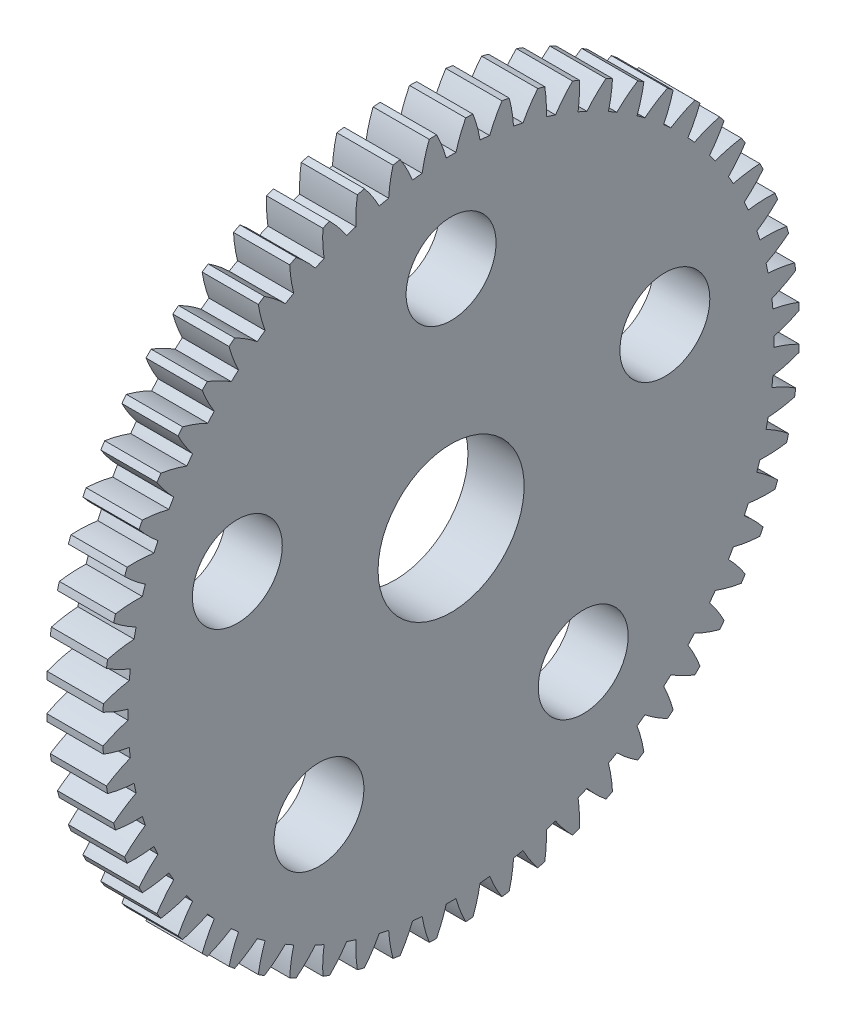
SolidWorks part; units mm, degrees
ref_plane "Plane1" through (0, 0, 0) normal (0, 0, 1) x (1, 0, 0)
ref_plane "Plane2" through (0, 0, 0) normal (0, 1, 0) x (1, 0, 0)
ref_plane "Plane3" through (0, 0, 0) normal (1, 0, 0) x (0, 0, -1)
sketch "HoldingSke" plane through (0, 0, 0) normal (0, 1, 0) x (1, 0, 0)
  line L0 (0, 0) -> (0.5, -0.866)
  line L1 (-15, 0) -> (100, 0) construction
  line L2 (0, 0) -> (-2.1039, 2.3779)
  line L3 (0, 0) -> (-11.863, 4.5341)
  line L4 (0, 0) -> (4.318, 7.479)
  line L5 (0, 0) -> (-46.8476, -17.4728)
  line L6 (0, 0) -> (-4.1448, -2.7965)
  line L7 (-2.1039, 2.3779) -> (8.6586, 51.2059)
  line L8 (-76.2, 54.61) -> (-75.7, 54.61)
  line L9 (-71.009, 38.7566) -> (-53.1078, 45.2721)
  line L10 (-76.2, 71.12) -> (104.1128, 71.12)
  line L11 (0, 0) -> (-5, 0)
  line L12 (-76.2, 101.6) -> (-76.162, 101.6)
  line L13 (24.9733, 27.94) -> (52.9518, 28.4284)
  line L14 (24.9733, 27.94) -> (24.9743, 27.94)
  line L15 (24.9733, 27.94) -> (100.4006, 29.5858)
  line L16 (-63.627, -1) -> (-12.827, -1)
  circle A0 centre (0, 0) radius 1.5
  circle A1 centre (0, 0) radius 28.749
  circle A2 centre (0, 0) radius 37.5
  circle A3 centre (0, 0) radius 1.5
  dimension "MHD" = 57.498
  dimension "Hub_dia" = 75
  dimension "Bore" = 3
  dimension "MBD" = 3
  dimension "Num_teeth" = 60
  dimension "Pitch" = 1
  dimension "Overall_len" = 50
  dimension "Show_teeth" = 60
  dimension "Thickness" = 5
  dimension "OAL" = 50.0001
  dimension "T_dim" = 0.5
  dimension "Ap" = 20
  dimension "H" = 19.05
  dimension "Pitch_radius" = 180.3128
  dimension "Width" = 5
  dimension "Backlash" = 0.038
  dimension "Addendum_fac" = 1
  dimension "Dedendum_fac" = 1.25
  dimension "Clearance_fac" = 0.25
  dimension "Dedendum_add" = 0.001
  dimension "Module" = 1
sketch "BasProSke" plane through (0, 0, 0) normal (0, 1, 0) x (1, 0, 0)
  line L0 (-10, 0) -> (60, 0) construction
  line L1 (0, 0) -> (0, 31)
  line L2 (0, 0) -> (5, 0)
  line L3 (5, 0) -> (5, 31)
  line L4 (5, 31) -> (0, 31)
  dimension "Thickness" = 5
  dimension "Diameter" = 62
revolve "Base-Revolve" add sketch "BasProSke" angle 360 about L0
sketch "TooCutSke" plane through (0, 0, 0) normal (1, 0, 0) x (0, 0, -1)
  line L1 (0, 0) -> (0, 107) construction
  line L2 (0, 0) -> (-0.8518, 29.9879) construction
  line L3 (0, 0) -> (-3.1393, 59.9006) construction
  line L4 (-0.8518, 29.9879) -> (-1.5696, 29.9503) construction
  arc A0 (0.4302, 28.7458) -> (-0.4302, 28.7458) centre (0, 0) ccw
  arc A1 (1.3127, 30.9976) -> (-1.3127, 30.9976) centre (0, 0) ccw
  circle A2 centre (0, 0) radius 30 construction
  circle A3 centre (0, 0) radius 28.1908 construction
  arc A4 (-0.4302, 28.7458) -> (-1.3127, 30.9976) centre (-11.9871, 25.5153) ccw
  arc A5 (1.3127, 30.9976) -> (0.4302, 28.7458) centre (11.9871, 25.5153) ccw
  dimension "Root_dia" = 57.498
  dimension "Overcut_dia" = 62.0508
  dimension "Pitch_dia" = 60
  dimension "Base_dia" = 56.3816
  dimension "Flank_rad" = 12
  dimension "Half_ang" = 3
  dimension "Half_CT" = 0.7188
extrude "ToothCut" cut sketch "TooCutSke" along normal through all
fillet "Breaks" [suppressed] radius 0.02
fillet "RootFillets" [suppressed] radius 0.251
pattern_circular "TeethCuts" count 60 over 360 about axis through (0, 0, 0) along (1, 0, 0) of "ToothCut", "RootFillets", "Breaks"
sketch "HubNeaOneSke" plane through (0, 0, 0) normal (-1, 0, 0) x (0, 0, 1)
  circle A0 centre (0, 0) radius 28.749
  dimension "Diameter" = 57.498
extrude "HubNearOne" [suppressed] add sketch "HubNeaOneSke" along normal blind 45.0001
sketch "HubNeaBotSke" plane through (0, 0, 0) normal (-1, 0, 0) x (0, 0, 1)
  circle A0 centre (0, 0) radius 28.749
  dimension "Diameter" = 57.498
extrude "HubNearBoth" [suppressed] add sketch "HubNeaBotSke" along normal blind 22.5
ref_plane "FarPln" through (5, 0, 0) normal (1, 0, 0) x (0, 0, -1)
sketch "HubFarSke" plane through (5, 0, 0) normal (1, 0, 0) x (0, 0, -1)
  circle A0 centre (0, 0) radius 28.749
  dimension "Diameter" = 57.498
extrude "HubFar" [suppressed] add sketch "HubFarSke" along normal blind 22.5
sketch "BorSke" plane through (0, 0, 0) normal (1, 0, 0) x (0, 0, -1)
  circle A0 centre (0, 0) radius 6.5
  dimension "Diameter" = 13
extrude "Bore" cut sketch "BorSke" along normal mid plane 100.0001
sketch "KeySke" plane through (0, 0, 0) normal (1, 0, 0) x (0, 0, -1)
  line L0 (-0.6, 0) -> (-0.6, 2)
  line L1 (-0.6, 2) -> (0.6, 2)
  line L2 (0.6, 2) -> (0.6, 0)
  line L3 (0, 0) -> (0, 34) construction
  line L4 (-0.6, 0) -> (0.6, 0)
  dimension "Offset" = 2
  dimension "Width" = 1.2
extrude "Keyway" [suppressed] cut sketch "KeySke" along normal mid plane 100.0001
sketch "草图1" plane through (5, 0, 0) normal (1, 0, 0) x (0, 0, -1)
  circle A0 centre (0, 20) radius 4
  circle A1 centre (0, 0) radius 6.5 construction
  circle A2 centre (19.0211, 6.1803) radius 4
  circle A3 centre (11.7557, -16.1803) radius 4
  circle A4 centre (-11.7557, -16.1803) radius 4
  circle A5 centre (-19.0211, 6.1803) radius 4
  point P14 (0, 0)
  dimension "D1" = 8
  dimension "D2" = 20
  dimension "D3" = 5
extrude "切除-拉伸2" cut sketch "草图1" against normal blind 5
equation "' \"Module@HoldingSke\" = 6.35"
equation "' \"Num_teeth@HoldingSke\" = 12"
equation "' \"Ap@HoldingSke\" =  20"
equation "' \"Ap@HoldingSke\" = 20"
equation "' \"Width@HoldingSke\" = 0.5 * 25.4"
equation "' \"Hub_dia@HoldingSke\"= 1 * 25.4"
equation "' \"Hub_dia@HoldingSke\" = 1 * 25.4"
equation "' \"Overall_len@HoldingSke\" = 1.0 * 25.4"
equation "' \"Bore@HoldingSke\" = 0.75 * 25.4"
equation "' \"T_dim@HoldingSke\" = 0.1 * 25.4"
equation "' \"Width@KeySke\" = 0.25 * 25.4"
equation "' \"Show_teeth@HoldingSke\" = 13"
equation "' \"Backlash@HoldingSke\" = 0.009 * 25.4"
equation "' \"Addendum_fac@HoldingSke\" = 1.0"
equation "' \"Dedendum_fac@HoldingSke\" = 1.25"
equation "' \"Dedendum_add@HoldingSke\" = 0.00005 * 25.4"
equation "' \"Clearance_fac@HoldingSke\" = 0.25"
equation "\"Pitch@HoldingSke\" = 1 / \"Module@HoldingSke\""
equation "\"Overcut_dia@TooCutSke\" = (\"Num_teeth@HoldingSke\" + 2 * \"Addendum_fac@HoldingSke\") / \"Pitch@HoldingSke\" + 0.002 * 25.4"
equation "\"Pitch_dia@TooCutSke\" = \"Num_teeth@HoldingSke\" / \"Pitch@HoldingSke\""
equation "\"Base_dia@TooCutSke\" = \"Num_teeth@HoldingSke\" / \"Pitch@HoldingSke\" * cos((\"Ap@HoldingSke\"  * 3.14159265 / 180))"
equation "\"Root_dia@TooCutSke\" = (\"Num_teeth@HoldingSke\" + 2) / \"Pitch@HoldingSke\" - 2 * (\"Addendum_fac@HoldingSke\" + \"Dedendum_fac@HoldingSke\") / \"Pitch@HoldingSke\" - \"Dedendum_add@HoldingSke\" * 2"
equation "\"Half_ang@TooCutSke\" = 180 / \"Num_teeth@HoldingSke\""
equation "\"Half_CT@TooCutSke\" = \"Num_teeth@HoldingSke\" / \"Pitch@HoldingSke\" * sin((3.14159265 / 2 / \"Num_teeth@HoldingSke\")) / 2 - 7 * \"Backlash@HoldingSke\" / 4"
equation "\"Flank_rad@TooCutSke\" = \"Num_teeth@HoldingSke\" / \"Pitch@HoldingSke\" / 5"
equation "\"Radius@RootFillets\" = \"Clearance_fac@HoldingSke\" / \"Pitch@HoldingSke\" + \"Dedendum_add@HoldingSke\""
equation "\"Break_rad@Breaks\" = 0.02 / \"Pitch@HoldingSke\""
equation "\"Thickness@HoldingSke\" = \"Width@HoldingSke\""
equation "\"OAL@HoldingSke\" = \"Thickness@HoldingSke\""
equation "\"MHD@HoldingSke\" = (\"Num_teeth@HoldingSke\" + 2) / \"Pitch@HoldingSke\" - 2 * (\"Addendum_fac@HoldingSke\" + \"Dedendum_fac@HoldingSke\")  / \"Pitch@HoldingSke\" - \"Dedendum_add@HoldingSke\" * 2"
equation "\"MBD@HoldingSke\" = (\"Num_teeth@HoldingSke\" + 2) / \"Pitch@HoldingSke\" - 2 * (\"Addendum_fac@HoldingSke\" + \"Dedendum_fac@HoldingSke\")  / \"Pitch@HoldingSke\" - \"Dedendum_add@HoldingSke\" * 2 - 0.002 * 25.4"
equation "\"MHD@HoldingSke\" = ((sgn( \"MHD@HoldingSke\" - \"Hub_dia@HoldingSke\" )-1)*( \"MHD@HoldingSke\" - \"Hub_dia@HoldingSke\" ))/-2+ \"Hub_dia@HoldingSke\""
equation "\"MBD@HoldingSke\" = ((sgn( \"MBD@HoldingSke\" - \"Bore@HoldingSke\" )-1)*( \"MBD@HoldingSke\" - \"Bore@HoldingSke\" ))/-2+ \"Bore@HoldingSke\""
equation "\"OAL@HoldingSke\" = ((sgn( \"OAL@HoldingSke\" - \"Overall_len@HoldingSke\" )+1)*( \"OAL@HoldingSke\" - \"Overall_len@HoldingSke\" ))/2 + \"Overall_len@HoldingSke\" + 0.000002 * 25.4"
equation "\"Num_teeth@TeethCuts\" = int( \"Show_teeth@HoldingSke\" ) + 1"
equation "\"Num_teeth@TeethCuts\" = ((sgn( \"Num_teeth@TeethCuts\" - \"Num_teeth@HoldingSke\" )-1)*( \"Num_teeth@TeethCuts\" - \"Num_teeth@HoldingSke\" ))/-2+ \"Num_teeth@HoldingSke\""
equation "\"Num_teeth@TeethCuts\" = ((sgn( \"Num_teeth@TeethCuts\" - 2.0)+1)*( \"Num_teeth@TeethCuts\" - 2.0))/2 +2.0"
equation "\"Angle@TeethCuts\" = 360.0 / \"Num_teeth@HoldingSke\""
equation "\"Diameter@BasProSke\" = (\"Num_teeth@HoldingSke\" + 2 * \"Addendum_fac@HoldingSke\") / \"Pitch@HoldingSke\""
equation "\"Thickness@BasProSke\"  = \"Thickness@HoldingSke\""
equation "' \"Fillet_rad@BasProSke\" =  \"Thickness@HoldingSke\" * 0.05"
equation "' \"Fillet_rad@BasProSke\" = \"Thickness@HoldingSke\" * 0.05"
equation "\"MHD@HoldingSke\" = ((sgn( \"MHD@HoldingSke\" - \"Root_dia@TooCutSke\" )-1)*( \"MHD@HoldingSke\" - \"Root_dia@TooCutSke\" ))/-2+ \"Root_dia@TooCutSke\""
equation "\"Diameter@HubNeaOneSke\" = \"MHD@HoldingSke\""
equation "\"Length@HubNearOne\" = \"OAL@HoldingSke\" - \"Thickness@BasProSke\""
equation "\"Diameter@HubNeaBotSke\" = \"MHD@HoldingSke\""
equation "\"Length@HubNearBoth\" = ( \"OAL@HoldingSke\" - \"Thickness@BasProSke\" ) / 2.0"
equation "\"Thickness@FarPln\" = \"Thickness@BasProSke\""
equation "\"Diameter@HubFarSke\" = \"MHD@HoldingSke\""
equation "\"Length@HubFar\" = ( \"OAL@HoldingSke\" - \"Thickness@BasProSke\" ) / 2.0"
equation "\"D1@Bore\" = \"OAL@HoldingSke\" * 2.0"
equation "\"D1@Keyway\" = \"OAL@HoldingSke\" * 2.0"
equation "\"Offset@KeySke\" = \"T_dim@HoldingSke\" + \"MBD@HoldingSke\" / 2.0"
